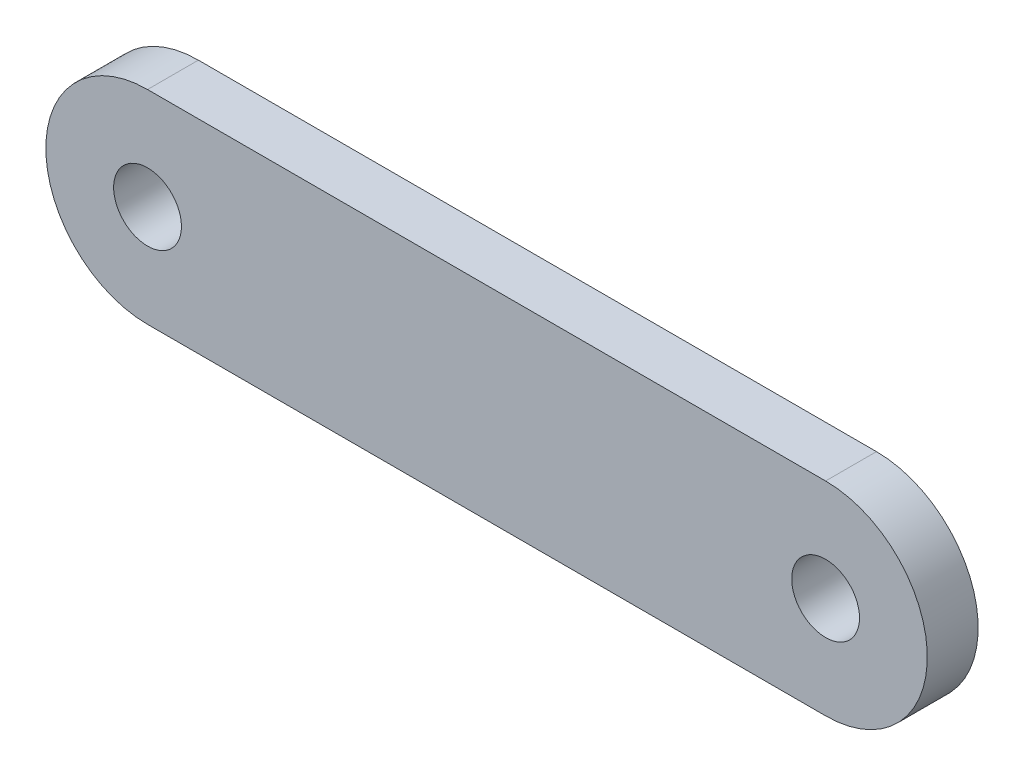
SolidWorks part; units mm, degrees
ref_plane "Front Plane" through (0, 0, 0) normal (0, 0, 1) x (1, 0, 0)
ref_plane "Top Plane" through (0, 0, 0) normal (0, 1, 0) x (1, 0, 0)
ref_plane "Right Plane" through (0, 0, 0) normal (1, 0, 0) x (0, 0, -1)
sketch "Sketch1" plane through (0, 0, 0) normal (0, 0, 1) x (1, 0, 0)
  line L0 (-35.3127, 0) -> (4.6873, 0) construction
  line L1 (-35.3127, 6) -> (4.6873, 6)
  line L2 (-35.3127, -6) -> (4.6873, -6)
  arc A0 (-35.3127, 6) -> (-35.3127, -6) centre (-35.3127, 0) ccw
  arc A1 (4.6873, -6) -> (4.6873, 6) centre (4.6873, 0) ccw
  circle A2 centre (-35.3127, 0) radius 2
  circle A3 centre (4.6873, 0) radius 2
  point P3 (-15.3127, 0)
  dimension "D3" = 4
  dimension "D4" = 4
  dimension "D1" = 40
  dimension "D2" = 12
extrude "Boss-Extrude3" add sketch "Sketch1" along normal blind 3
